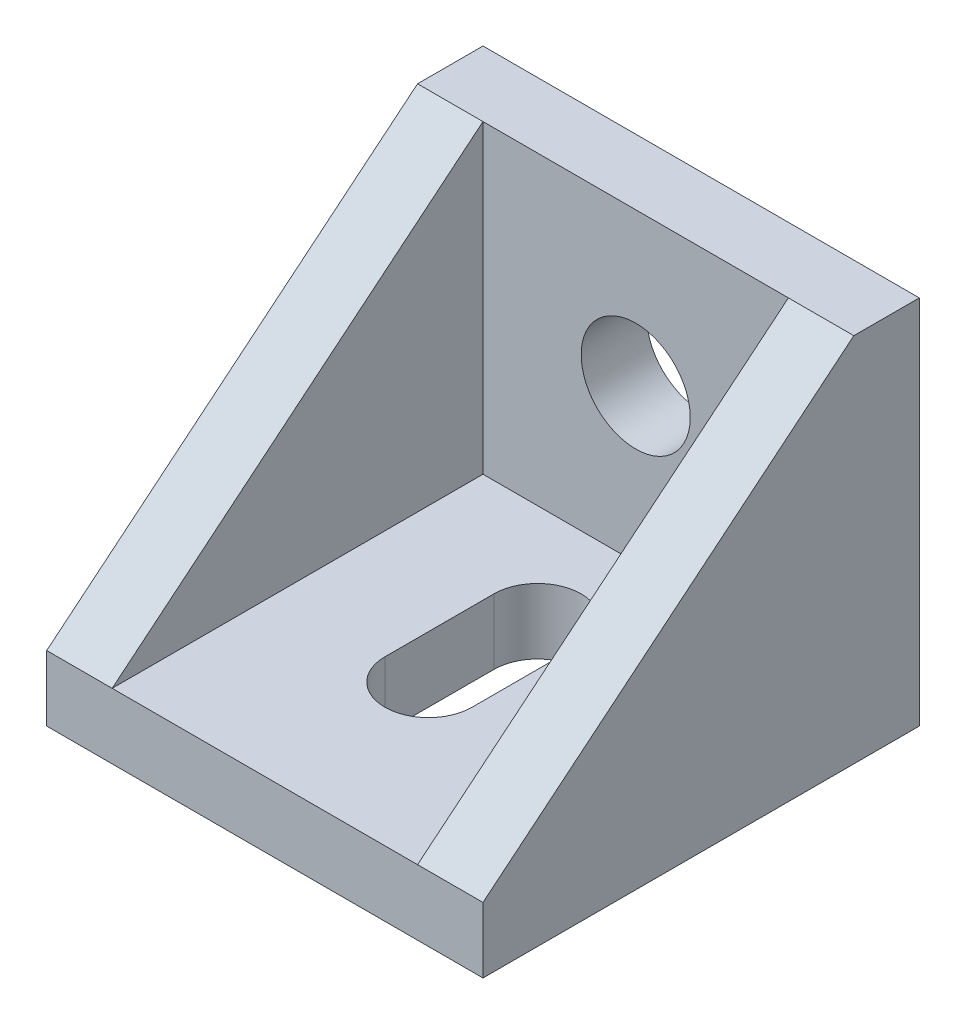
SolidWorks part; units mm, degrees
material "Plain Carbon Steel"
ref_plane "Front Plane" through (0, 0, 0) normal (0, 0, 1) x (1, 0, 0)
ref_plane "Top Plane" through (0, 0, 0) normal (0, 1, 0) x (1, 0, 0)
ref_plane "Right Plane" through (0, 0, 0) normal (1, 0, 0) x (0, 0, -1)
sketch "Sketch1" plane through (0, 0, 0) normal (0, 1, 0) x (1, 0, 0)
  line L1 (10, -10) -> (-10, -10)
  line L2 (10, -10) -> (10, 10)
  line L3 (10, 10) -> (-10, 10)
  line L4 (-10, -10) -> (-10, 10)
  line L5 (10, -10) -> (-10, 10) construction
  line L6 (10, 10) -> (-10, -10) construction
  point P0 (0, 0)
  dimension "D1" = 20
extrude "Boss-Extrude1" add sketch "Sketch1" along normal blind 3
sketch "Sketch2" plane through (0, 0, -10) normal (0, 0, -1) x (-1, 0, 0)
  line L0 (10, 3) -> (10, 0) construction
  line L1 (-10, 0) -> (10, 0)
  line L2 (-10, 0) -> (-10, 17)
  line L3 (-10, 17) -> (10, 17)
  line L4 (10, 0) -> (10, 17)
  dimension "D1" = 17
extrude "Boss-Extrude2" add sketch "Sketch2" against normal blind 3
sketch "Sketch3" plane through (10, 0, 0) normal (1, 0, 0) x (0, 0, -1)
  line L0 (7, 17) -> (7, 3) construction
  line L1 (-10, 3) -> (7, 3) construction
  line L2 (7, 17) -> (7, 3)
  line L3 (-10, 3) -> (7, 3)
  line L4 (7, 17) -> (-10, 3)
extrude "Boss-Extrude3" add sketch "Sketch3" against normal blind 3
mirror "Mirror1" about plane through (0, 0, 0) normal (1, 0, 0) of "Boss-Extrude3"
sketch "Sketch4" plane through (0, 0, -7) normal (0, 0, 1) x (1, 0, 0)
  line L0 (-7, 17) -> (7, 3) construction
  line L1 (7, 3) -> (7, 17) construction
  line L2 (7, 17) -> (-7, 3) construction
  circle A0 centre (0, 10) radius 2.5
  point P4 (0, 10)
  dimension "D1" = 5
extrude "Cut-Extrude1" cut sketch "Sketch4" against normal through all
sketch "Sketch5" plane through (0, 3, 0) normal (0, 1, 0) x (1, 0, 0)
  line L0 (0, -2.5) -> (0, 2.5) construction
  line L1 (-2, -2.5) -> (-2, 2.5)
  line L2 (2, -2.5) -> (2, 2.5)
  arc A0 (-2, -2.5) -> (2, -2.5) centre (0, -2.5) ccw
  arc A1 (2, 2.5) -> (-2, 2.5) centre (0, 2.5) ccw
  point P2 (0, 0)
  dimension "D1" = 2
  dimension "D2" = 5
extrude "Cut-Extrude2" cut sketch "Sketch5" against normal blind 4
